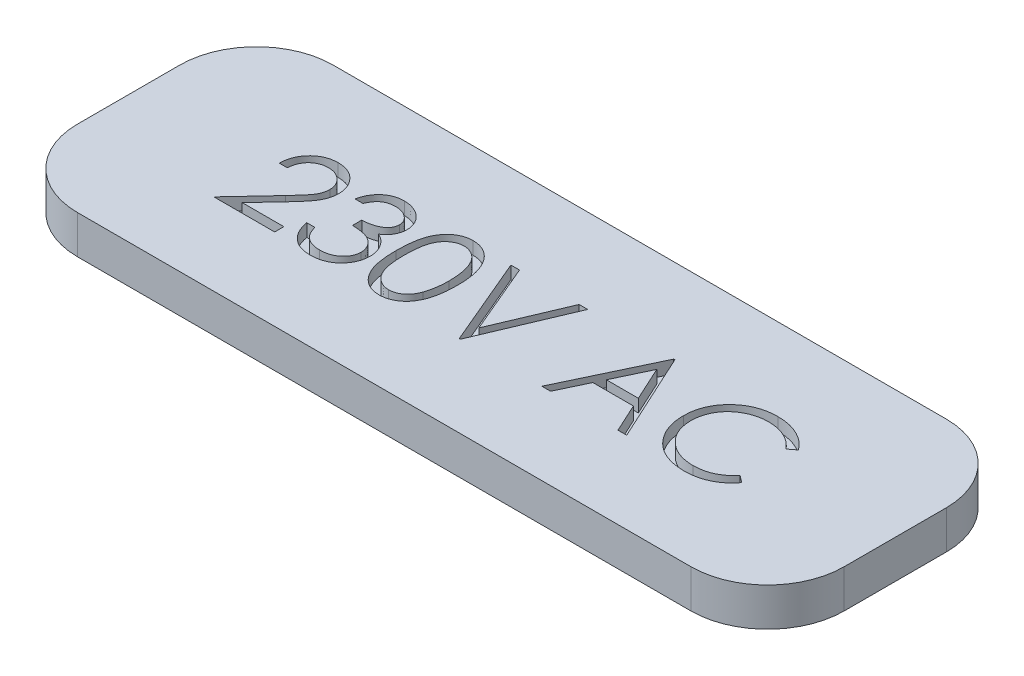
SolidWorks part; units mm, degrees
material "ABS"
ref_plane "Front Plane" through (0, 0, 0) normal (0, 0, 1) x (1, 0, 0)
ref_plane "Top Plane" through (0, 0, 0) normal (0, 1, 0) x (1, 0, 0)
ref_plane "Right Plane" through (0, 0, 0) normal (1, 0, 0) x (0, 0, -1)
sketch "Sketch1" plane through (0, 0, 0) normal (0, 1, 0) x (1, 0, 0)
  line L1 (0, 0) -> (-30, 0)
  line L2 (0, 0) -> (0, -10)
  line L3 (0, -10) -> (-30, -10)
  line L4 (-30, 0) -> (-30, -10)
  dimension "D1" = 10
  dimension "D2" = 30
extrude "Boss-Extrude1" add sketch "Sketch1" along normal blind 1.5
fillet "Fillet1" radius 3 4 edges at (0, 0.75, 10) (0, 0.75, 0) (-30, 0.75, 10) (-30, 0.75, 0)
sketch "Sketch2" plane through (0, 1.5, 0) normal (0, 1, 0) x (1, 0, 0)
  line L1 (-27, -10) -> (-3, -10) construction
  line L2 (-30, -3) -> (-30, -7) construction
  text T0 "230V AC"
  dimension "D1" = 3.2
  dimension "D2" = 5
extrude "Cut-Extrude1" cut sketch "Sketch2" against normal blind 0.5
